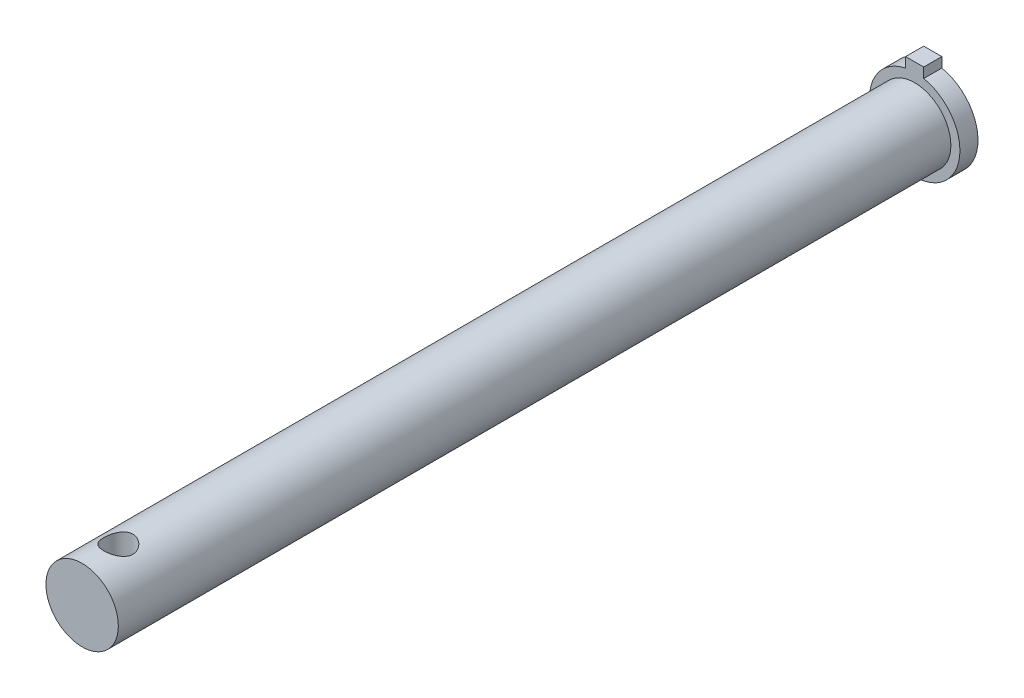
SolidWorks part; units mm, degrees
ref_plane "Front Plane" through (0, 0, 0) normal (0, 0, 1) x (1, 0, 0)
ref_plane "Top Plane" through (0, 0, 0) normal (0, 1, 0) x (1, 0, 0)
ref_plane "Right Plane" through (0, 0, 0) normal (1, 0, 0) x (0, 0, -1)
sketch "Sketch1" plane through (0, 0, 0) normal (0, 0, 1) x (1, 0, 0)
  circle A0 centre (0, 0) radius 12.5
  dimension "D1" = 25
extrude "Boss-Extrude1" add sketch "Sketch1" along normal blind 5
sketch "Sketch3" plane through (0, 0, 5) normal (0, 0, 1) x (1, 0, 0)
  circle A0 centre (0, 0) radius 10
  dimension "D1" = 20
extrude "Boss-Extrude2" add sketch "Sketch3" along normal blind 230
ref_plane "Plane1" through (0, 0, 225) normal (0, 0, 1) x (1, 0, 0)
sketch "Sketch4" plane through (0, 0, 0) normal (0, 1, 0) x (1, 0, 0)
  line L0 (-10, -235) -> (10, -235) construction
  circle A0 centre (0, -225) radius 4
  dimension "D1" = 8
  dimension "D2" = 10
extrude "Cut-Extrude1" cut sketch "Sketch4" against normal through all and the other way through all
ref_plane "Plane3" through (0, 15, 0) normal (0, 1, 0) x (1, 0, 0)
sketch "Sketch5" plane through (0, 15, 0) normal (0, 1, 0) x (1, 0, 0)
  line L1 (-2.5, -5) -> (2.5, -5)
  line L2 (-2.5, -5) -> (-2.5, 0)
  line L3 (-2.5, 0) -> (2.5, 0)
  line L4 (2.5, -5) -> (2.5, 0)
  line L5 (-2.5, -5) -> (2.5, 0) construction
  line L6 (-2.5, 0) -> (2.5, -5) construction
  point P0 (0, -2.5)
  dimension "D1" = 5
  dimension "D2" = 5
  dimension "D3" = 2.5
  dimension "D4" = 0
extrude "Boss-Extrude3" add sketch "Sketch5" against normal up to next
